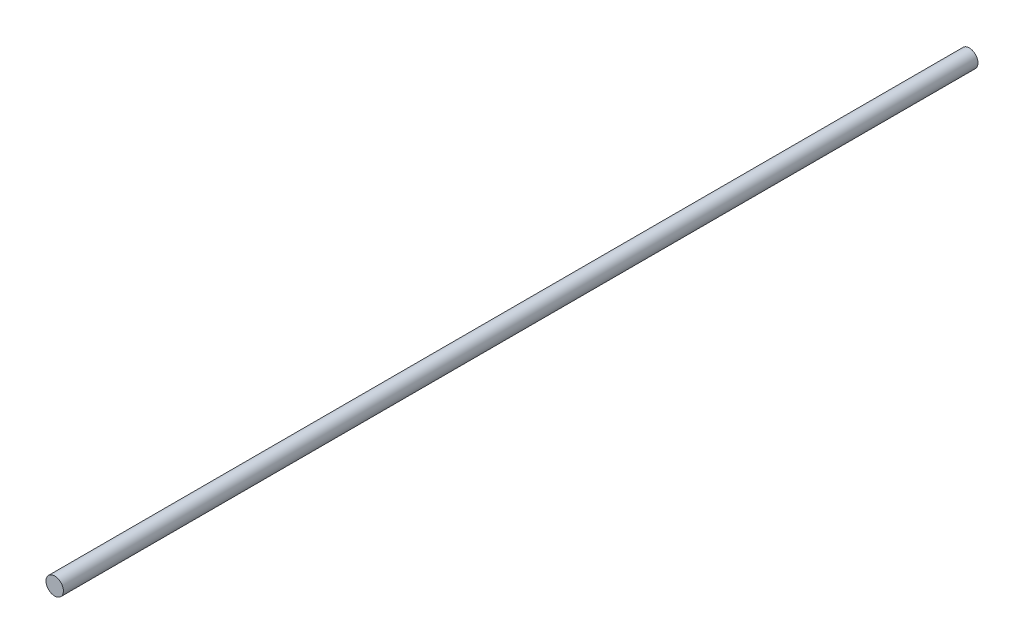
SolidWorks part; units mm, degrees
ref_plane "Front Plane" through (0, 0, 0) normal (0, 0, 1) x (1, 0, 0)
ref_plane "Top Plane" through (0, 0, 0) normal (0, 1, 0) x (1, 0, 0)
ref_plane "Right Plane" through (0, 0, 0) normal (1, 0, 0) x (0, 0, -1)
sketch "Sketch1" plane through (0, 0, 0) normal (0, 0, 1) x (1, 0, 0)
  circle A0 centre (0, 0) radius 20
  dimension "D1" = 40
extrude "Boss-Extrude1" add sketch "Sketch1" along normal blind 2100
